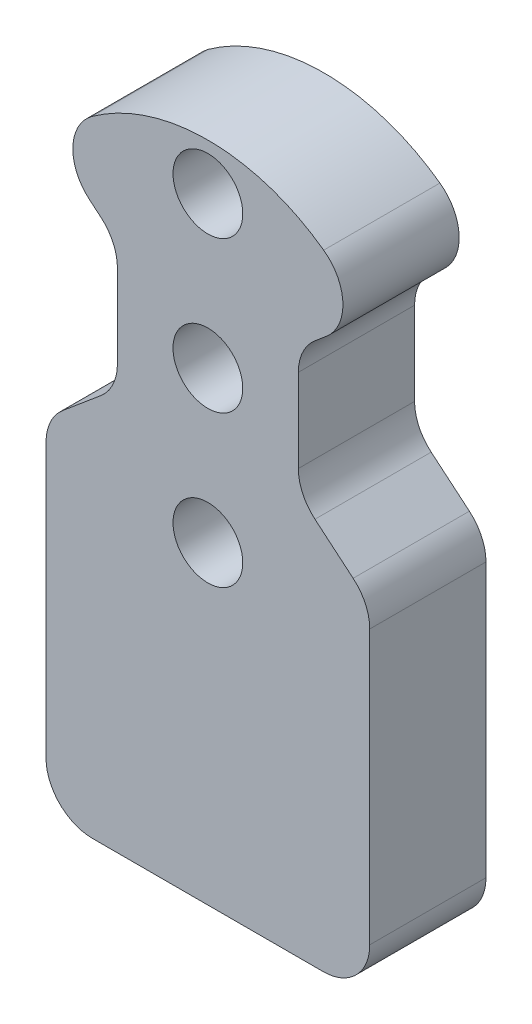
SolidWorks part; units mm, degrees
material "Thornel Mat VMA"
ref_plane "前视基准面" through (0, 0, 0) normal (0, 0, 1) x (1, 0, 0)
ref_plane "上视基准面" through (0, 0, 0) normal (0, 1, 0) x (1, 0, 0)
ref_plane "右视基准面" through (0, 0, 0) normal (1, 0, 0) x (0, 0, -1)
sketch "草图1" plane through (0, 0, 0) normal (0, 0, 1) x (1, 0, 0)
  circle A0 centre (0, 0) radius 8.5
  dimension "D1" = 17
extrude "凸台-拉伸1" add sketch "草图1" along normal blind 5
sketch "草图2" plane through (0, 0, 5) normal (0, 0, 1) x (1, 0, 0)
  circle A0 centre (0, 0) radius 6.5 construction
  circle A1 centre (0, 6.5) radius 1.5
  circle A2 centre (0, -6.5) radius 1.5
  dimension "D1" = 13
  dimension "D2" = 3
extrude "切除-拉伸1" cut sketch "草图2" against normal blind 5
sketch "草图3" plane through (0, 0, 0) normal (0, 0, -1) x (-1, 0, 0)
  line L0 (0, 0) -> (11.6987, 0) construction
  line L1 (0, 0) -> (6.9628, 4.8754)
  line L2 (0, 0) -> (6.9628, -4.8754)
  circle A0 centre (0, 0) radius 4.75
  circle A1 centre (0, 0) radius 8.5
  circle M17 centre (0, 0) radius 8.5
  dimension "D1" = 9.5
  dimension "D2" = 17
  dimension "D3" = 35
  dimension "D4" = 35
extrude "切除-拉伸2" cut sketch "草图3" against normal through all contours A0 L0 A1 L1 | L0 A0 L2 M17
mirror "镜向1" about plane through (0, 0, 0) normal (1, 0, 0) of "切除-拉伸2"
sketch "草图4" plane through (0, 0, 0) normal (0, 0, -1) x (-1, 0, 0)
  line L2 (-6.9628, 4.8754) -> (-6.9628, -20)
  line L3 (-6.9628, -20) -> (6.9628, -20)
  line L4 (6.9628, 4.8754) -> (6.9628, -20)
  line L5 (-2.7947, 8.0274) -> (6.9628, -20) construction
  line L6 (-6.9628, -20) -> (2.7947, 8.0274) construction
  circle A0 centre (0, 0) radius 8.5
  arc M9 (-6.9628, -4.8754) -> (6.9628, -4.8754) centre (0, 0) ccw
  dimension "D1" = 17
  dimension "D2" = 13.9256
  dimension "D3" = 20
extrude "凸台-拉伸2" add sketch "草图4" against normal blind 5 separate body contours L4 L2 L3 M9 | A0
combine bodies "组合1" operation type add bodies to combine 109 110 110
sketch "草图6" plane through (0, 0, 0) normal (0, 0, -1) x (-1, 0, 0)
  line L0 (-3.891, 2.7245) -> (-3.891, -2.7245)
  line L1 (3.891, -2.7245) -> (3.891, 2.7245)
  line L2 (3.891, 2.7245) -> (6.7698, 5.1401)
  line L3 (-3.891, 2.7245) -> (-6.7698, 5.1401)
  line L4 (-3.891, -2.7245) -> (-6.9628, -5.3021)
  line L5 (3.891, -2.7245) -> (6.9628, -5.3021)
  line L7 (-3.891, -2.7245) -> (-6.9628, -4.8754)
  line L8 (-6.9628, -4.8754) -> (-6.9628, -20)
  line L9 (-6.9628, -20) -> (6.9628, -20)
  line L10 (6.9628, -20) -> (6.9628, -4.8754)
  line L11 (6.9628, -4.8754) -> (3.891, -2.7245)
  line L12 (3.891, 2.7245) -> (6.9628, 4.8754)
  line L13 (-6.9628, 4.8754) -> (-3.891, 2.7245)
  line L14 (-3.891, -2.7245) -> (-6.9628, -4.8754)
  line L15 (-6.9628, -4.8754) -> (-6.9628, -20)
  line L16 (-6.9628, -20) -> (6.9628, -20)
  line L17 (6.9628, -20) -> (6.9628, -4.8754)
  line L18 (6.9628, -4.8754) -> (3.891, -2.7245)
  line L19 (3.891, 2.7245) -> (6.9628, 4.8754)
  line L20 (-6.9628, 4.8754) -> (-3.891, 2.7245)
  circle A0 centre (0, 0) radius 1.5
  arc A3 (3.891, -2.7245) -> (3.891, 2.7245) centre (0, 0) ccw
  arc A4 (6.9628, 4.8754) -> (-6.9628, 4.8754) centre (0, 0) ccw
  arc A5 (-3.891, 2.7245) -> (-3.891, -2.7245) centre (0, 0) ccw
  arc A6 (3.891, -2.7245) -> (3.891, 2.7245) centre (0, 0) ccw
  arc A7 (6.9628, 4.8754) -> (-6.9628, 4.8754) centre (0, 0) ccw
  arc A8 (-3.891, 2.7245) -> (-3.891, -2.7245) centre (0, 0) ccw
  line M17 (-3.891, -2.7245) -> (-6.9628, -4.8754)
  line M18 (-6.9628, -4.8754) -> (-6.9628, -20)
  line M20 (6.9628, -20) -> (6.9628, -4.8754)
  line M21 (6.9628, -4.8754) -> (3.891, -2.7245)
  arc M22 (3.891, -2.7245) -> (3.891, 2.7245) centre (0, 0) ccw
  line M23 (3.891, 2.7245) -> (6.9628, 4.8754)
  arc M24 (6.9628, 4.8754) -> (-6.9628, 4.8754) centre (0, 0) ccw
  line M25 (-6.9628, 4.8754) -> (-3.891, 2.7245)
  arc M26 (-3.891, 2.7245) -> (-3.891, -2.7245) centre (0, 0) ccw
  dimension "D6" = 3
  dimension "D2" = 5
  dimension "D3" = 5
  dimension "D4" = 5
  dimension "D5" = 5
  dimension "D1" = 0
extrude "切除-拉伸3" cut sketch "草图6" against normal through all contours L0 M26 | L1 M22 | A0 | L4 M17 M18 | L5 M21 M20 | L2 M23 M24 | L3 M25 M24 | L14 L15 L16 L17 L18
fillet "圆角2" radius 2 10 edges at (3.891, 2.7245, 2.5) (3.891, -2.7245, 2.5) (6.9628, -5.3021, 2.5) (6.9628, -20, 2.5) (-6.9628, -20, 2.5) (-6.9628, -5.3021, 2.5) (-3.891, -2.7245, 2.5) (-3.891, 2.7245, 2.5) (-6.7698, 5.1401, 2.5) (6.7698, 5.1401, 2.5)
